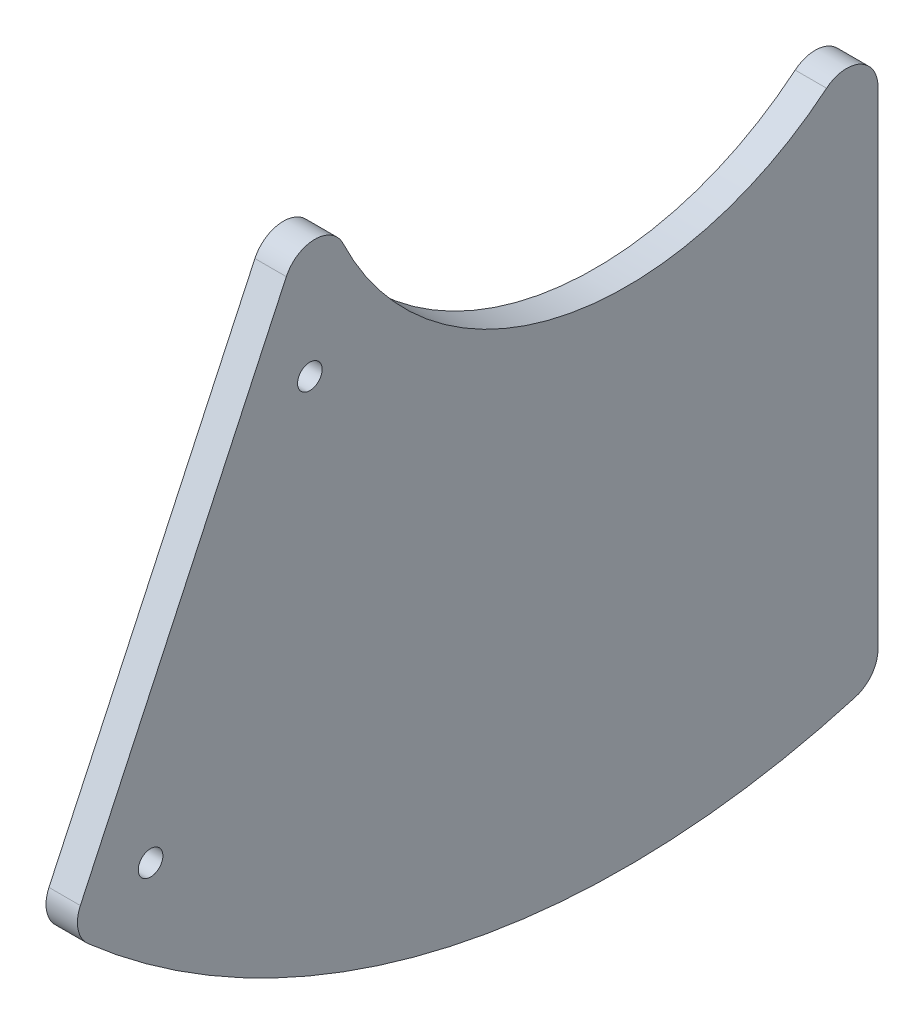
SolidWorks part; units mm, degrees
ref_plane "Front Plane" through (0, 0, 0) normal (1, 0, 0) x (0, 1, 0)
ref_plane "Top Plane" through (0, 0, 0) normal (0, 0, 1) x (0, 1, 0)
ref_plane "Right Plane" through (0, 0, 0) normal (0, 1, 0) x (-1, 0, 0)
sketch "Sketch1" plane through (0, 0, 0) normal (1, 0, 0) x (0, 1, 0)
  line L6 (0, 0) -> (21.469, 46.0404) construction
  line L7 (0, -50.8) -> (-157.0903, -50.8) construction
  line L8 (0, 0) -> (-142.3722, 66.3892) construction
  line L9 (21.469, 46.0404) -> (-120.9032, 112.4297) construction
  line L10 (-142.3722, 66.3892) -> (-120.9032, 112.4297) construction
  line L11 (-13.0613, 62.1422) -> (-120.9032, 112.4297)
  line L12 (-38.1, -50.8) -> (-157.0903, -50.8)
  circle A0 centre (0, 0) radius 50.8 construction
  circle A3 centre (-113.5923, 12.7) radius 63.5 construction
  arc A4 (-13.0613, 62.1422) -> (-38.1, -50.8) centre (0, 0) ccw
  arc A5 (-120.9032, 112.4297) -> (-157.0903, -50.8) centre (0, 0) ccw
  dimension "D1" = 101.6
  dimension "D3" = 50.8
  dimension "D4" = 127
  dimension "D5" = 25
  dimension "D2" = 50.8
extrude "Boss-Extrude1" add sketch "Sketch1" along normal blind 6.35
sketch "Sketch2" plane through (6.35, 0, 0) normal (1, 0, 0) x (0, 1, 0)
  line L0 (-116.2645, 96.2537) -> (-129.4909, 102.4213) construction
  line L2 (-129.4909, 102.4213) -> (-116.2645, 96.2537) construction
  line L3 (-116.2645, 96.2537) -> (-47.2038, 64.0502) construction
  line L4 (-47.2038, 64.0502) -> (-29.9387, 55.9993) construction
  line L5 (-13.0613, 62.1422) -> (-120.9032, 112.4297) construction
  line L6 (0, 0) -> (-63.3056, 29.5199) construction
  line L7 (0, 0) -> (-142.3722, 66.3892) construction
  line L8 (-63.3056, 29.5199) -> (-47.2038, 64.0502) construction
  arc A2 (-120.9032, 112.4297) -> (-157.0903, -50.8) centre (0, 0) ccw construction
  arc A3 (-13.0613, 62.1422) -> (-38.1, -50.8) centre (0, 0) ccw construction
  point P0 (-116.2645, 96.2537)
  point P1 (-47.2038, 64.0502)
  dimension "D1" = 12.7
  dimension "D2" = 76.2
  dimension "D3" = 69.85
hole_wizard "#9 (0.196) Diameter Hole1" positions "Sketch2" profile "Sketch3" hole size "#9" standard "ANSI Inch" end condition through all
sketch "Sketch3" plane through (6.35, -116.2645, 96.2537) normal (0, 1, 0) x (0, 0, -1)
  line L0 (0, 0) -> (0, 6.35)
  line L1 (0, 6.35) -> (2.4892, 6.35)
  line L2 (2.4892, 6.35) -> (2.4892, 0)
  line L5 (2.4892, 0) -> (0, 0)
  line L11 (0, -6.35) -> (0, 107.95) construction
  dimension "Thru Hole Dia." = 4.9784
  dimension "Thru Hole Depth" = 6.35
fillet "Fillet1" radius 6.35 4 edges at (3.175, -120.9032, 112.4297) (3.175, -157.0903, -50.8) (3.175, -38.1, -50.8) (3.175, -13.0613, 62.1422)
